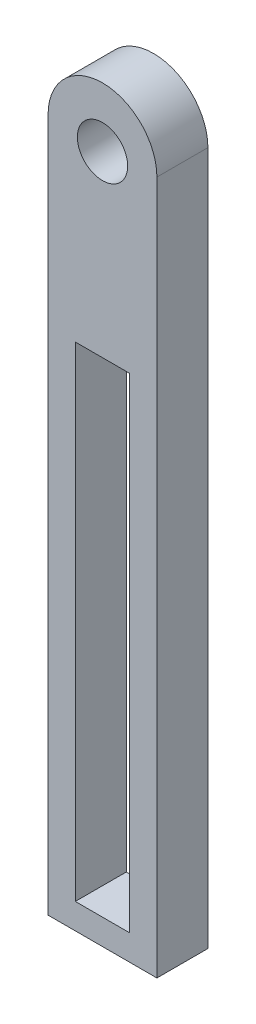
SolidWorks part; units mm, degrees
ref_plane "Front Plane" through (0, 0, 0) normal (0, 0, 1) x (1, 0, 0)
ref_plane "Top Plane" through (0, 0, 0) normal (0, 1, 0) x (1, 0, 0)
ref_plane "Right Plane" through (0, 0, 0) normal (1, 0, 0) x (0, 0, -1)
sketch "Sketch2" plane through (0, 0, 0) normal (0, 0, 1) x (1, 0, 0)
  line L1 (-22.2202, -20.4542) -> (-22.2202, -149.9942)
  line L2 (-1.9002, -20.4542) -> (-1.9002, -149.9942)
  line L3 (-22.2202, -149.9942) -> (-1.9002, -149.9942)
  line L4 (-12.0602, -20.4542) -> (-12.0602, -159.9573) construction
  line L10 (-17.1402, -145.2317) -> (-6.9802, -145.2317)
  line L11 (-17.1402, -145.2317) -> (-17.1402, -54.7442)
  line L12 (-17.1402, -54.7442) -> (-6.9802, -54.7442)
  line L13 (-6.9802, -145.2317) -> (-6.9802, -54.7442)
  line L14 (-17.1402, -145.2317) -> (-6.9802, -54.7442) construction
  line L15 (-17.1402, -54.7442) -> (-6.9802, -145.2317) construction
  arc A0 (-1.9002, -20.4542) -> (-22.2202, -20.4542) centre (-12.0602, -20.4542) ccw
  circle A2 centre (-12.0602, -21.4067) radius 4.699
  point P1 (-12.0602, -99.9879)
  point P11 (-12.0602, -10.2942)
  dimension "D6" = 11.1125
  dimension "D7" = 9.398
  dimension "D1" = 44.45
  dimension "D2" = 20.32
  dimension "D3" = 4.7625
  dimension "D4" = 10.16
  dimension "D5" = 139.7
extrude "Boss-Extrude1" add sketch "Sketch2" along normal blind 9.525
